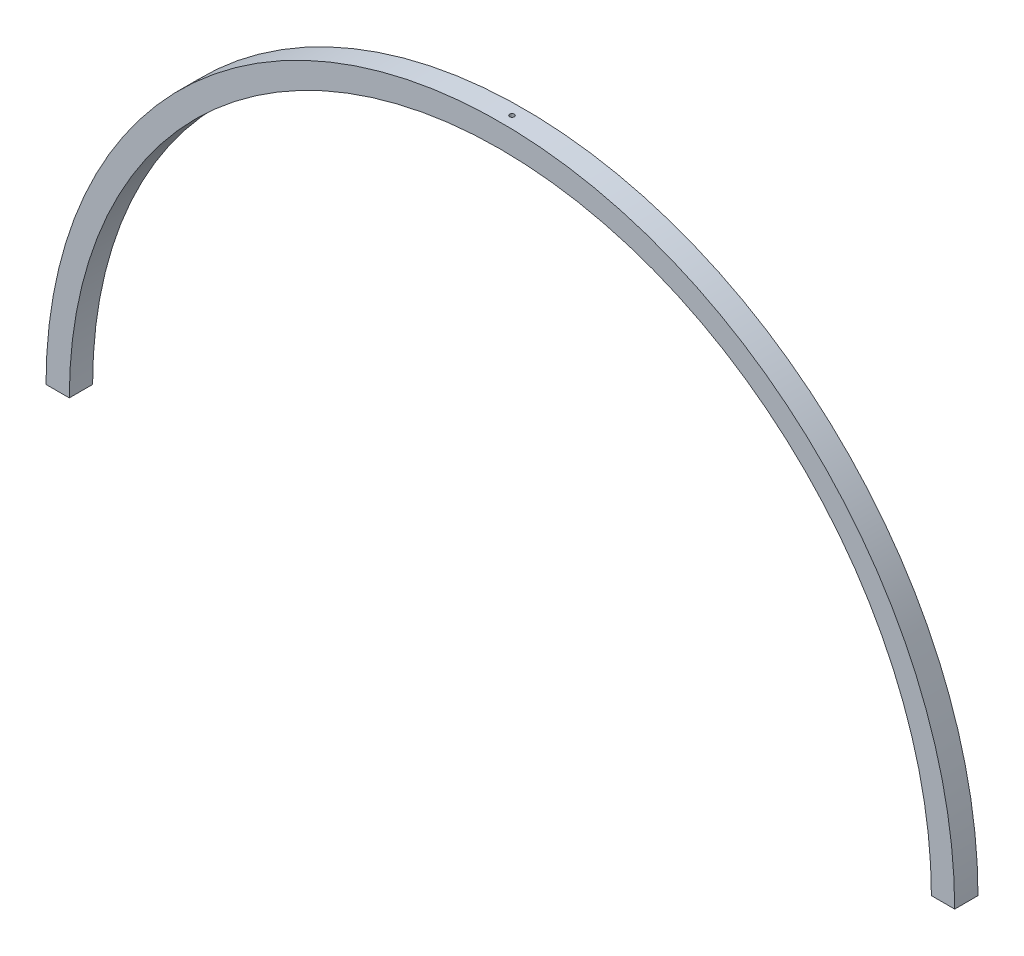
SolidWorks part; units mm, degrees
ref_plane "Ön Düzlem" through (0, 0, 0) normal (0, 0, 1) x (1, 0, 0)
ref_plane "Üst Düzlem" through (0, 0, 0) normal (0, 1, 0) x (1, 0, 0)
ref_plane "Sağ Düzlem" through (0, 0, 0) normal (1, 0, 0) x (0, 0, -1)
sketch "Çizim1" plane through (0, 0, 0) normal (0, 0, 1) x (1, 0, 0)
  line L0 (0, 0) -> (195, 0)
  line L1 (195, 0) -> (-195, 0)
  line L2 (0, 0) -> (0, 198.2659)
  line L3 (0, 198.2659) -> (0, 0)
  line L4 (0, -185) -> (0, -195.9461)
  line L5 (0, 0) -> (0, 46.1373)
  line L6 (0, 46.1373) -> (0, 261.5027)
  arc A0 (185, 0) -> (-185, 0) centre (0, 0) ccw
  arc A1 (195, 0) -> (-195, 0) centre (0, 0) ccw
  circle A2 centre (0, 0) radius 185
  circle A3 centre (0, 0) radius 195
extrude "Yükseklik-Ekstrüzyon2" add sketch "Çizim1" along normal blind 10 contours L1 A1
sketch "Çizim2" plane through (0, 0, 0) normal (0, -1, 0) x (1, 0, 0)
  line L0 (-195, 10) -> (-195, 0)
  line L1 (195, 10) -> (-195, 10) construction
  line L2 (-195, 10) -> (-195, 0) construction
  line L3 (195, 0) -> (-195, 0) construction
  line L4 (-195, 0) -> (195, 0)
  line L5 (195, 10) -> (195, 0) construction
  line L6 (195, 0) -> (195, 10)
  line L7 (195, 10) -> (-195, 10)
  line L8 (-195, 10) -> (195, 0)
  line L9 (-195, 0) -> (195, 10)
  line L10 (-195, 10) -> (0, 10)
  line L11 (0, 10) -> (0, 0)
  circle A0 centre (0, 5) radius 1
  circle A1 centre (0, 5) radius 0.9967
extrude "Kes-Ekstrüzyon-İnce1" cut sketch "Çizim2" against normal blind 10 thin contours L9 A1 L11 | L11 A1 L8 | L9 A1 L11 | L11 A1 L8
sketch "Çizim4" plane through (0, 10, 0) normal (0, -1, 0) x (1, 0, 0)
  line L0 (-9.7943, 10) -> (9.7943, 10)
  line L1 (-9.7943, 10) -> (-195, 10) construction
  line L2 (-9.7943, 10) -> (9.7943, 10) construction
  line L3 (9.7943, 10) -> (9.7943, 0)
  line L4 (-9.7943, 0) -> (9.7943, 0) construction
  line L5 (195, 0) -> (9.7943, 0) construction
  line L6 (9.7943, 0) -> (0, 0)
  line L7 (0, 0) -> (0, 10)
  line L8 (0, 10) -> (0, 0)
  line L9 (0, 5) -> (1.1948, 5)
  arc A0 (9.7943, 0) -> (9.7943, 10) centre (0, 5) ccw construction
  circle A1 centre (0, 5) radius 1
extrude "Kes-Ekstrüzyon16" cut sketch "Çizim4" against normal blind 240 contours A1
sketch "Çizim6" plane through (0, 0, 10) normal (0, 0, 1) x (1, 0, 0)
  circle A0 centre (0, 0) radius 185
extrude "Kes-Ekstrüzyon17" cut sketch "Çizim6" against normal blind 240
